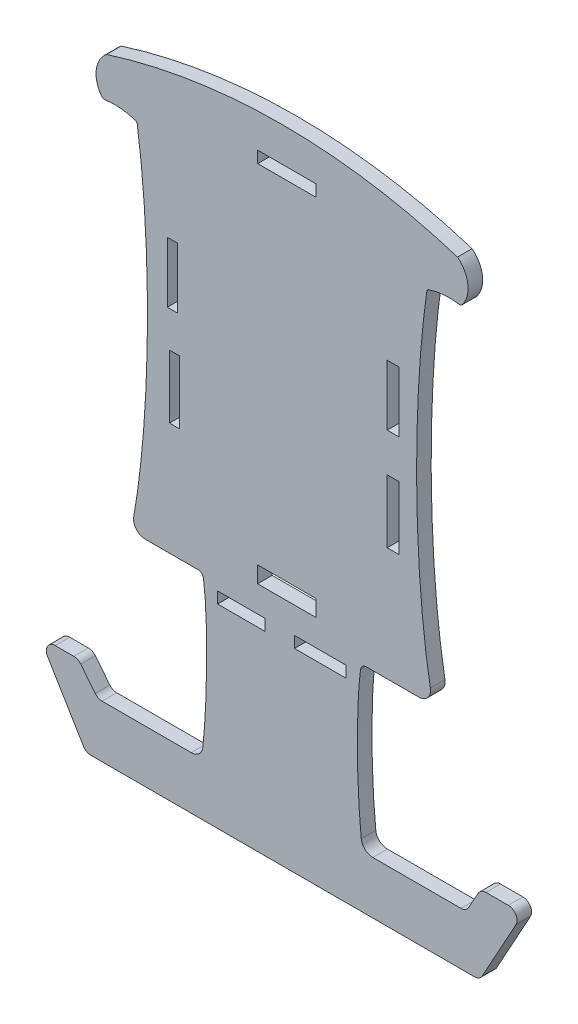
SolidWorks part; units mm, degrees
ref_plane "Front Plane" through (0, 0, 0) normal (0, 0, 1) x (1, 0, 0)
ref_plane "Top Plane" through (0, 0, 0) normal (0, 1, 0) x (1, 0, 0)
ref_plane "Right Plane" through (0, 0, 0) normal (1, 0, 0) x (0, 0, -1)
sketch "Sketch1" plane through (0, 0, 0) normal (0, 0, 1) x (1, 0, 0)
  line L0 (0, -123.7841) -> (0, 123.7841) construction
  line L1 (75.0482, 0) -> (-75.0482, 0) construction
  line L2 (-46.9089, -52.7206) -> (-28.9089, -52.7206)
  line L3 (-48.0489, 48.7999) -> (48.77, 48.7999) construction
  line L4 (-48.0489, 48.7999) -> (-48.0489, -52.7206) construction
  line L5 (-48.0489, -52.7206) -> (46.9089, -52.7206) construction
  line L6 (48.77, 48.7999) -> (48.77, -71.2001) construction
  line L7 (28.9089, -52.7206) -> (46.9089, -52.7206)
  line L8 (27.5, -123.7841) -> (27.5, 123.7841) construction
  line L13 (-27.5, -123.7841) -> (-27.5, 123.7841) construction
  line L14 (-62.2909, -89.7001) -> (10.6178, -89.7001) construction
  line L15 (-61.691, -108.2001) -> (-31.1278, -108.2001)
  line L17 (-65.5309, -126.2001) -> (65.9973, -126.2001)
  line L19 (61.3631, -108.2001) -> (31.1278, -108.2001)
  line L20 (63.9852, -106.6578) -> (67.2823, -100.727)
  line L21 (33.2, -123.7841) -> (33.2, 123.7841) construction
  line L22 (-33.2, -123.7841) -> (-33.2, 123.7841) construction
  line L23 (-68.204, 8.068) -> (119.1983, 8.068) construction
  line L24 (-8.3363, 82.068) -> (11.6637, 82.068)
  line L25 (-8.3363, 82.068) -> (-8.3363, 78.068)
  line L26 (-8.3363, 78.068) -> (11.6637, 78.068)
  line L27 (11.6637, 82.068) -> (11.6637, 78.068)
  line L28 (-8.3363, 8.068) -> (11.6637, 8.068) construction
  line L29 (4.2708, -55.6969) -> (21.9062, -55.6969)
  line L30 (36.0571, 41.9191) -> (40.1596, 41.9191)
  line L31 (36.0571, 41.9191) -> (36.0571, 21.1447)
  line L32 (36.0571, 21.1447) -> (40.1596, 21.1447)
  line L33 (40.1596, 41.9191) -> (40.1596, 21.1447)
  line L34 (36.0571, 7.8806) -> (40.1596, 7.8806)
  line L35 (36.0571, 7.8806) -> (36.0571, -13.7802)
  line L36 (36.0571, -13.7802) -> (40.1596, -13.7802)
  line L37 (40.1596, 7.8806) -> (40.1596, -13.7802)
  line L38 (-35.9066, 40.7148) -> (-39.3248, 40.7148)
  line L39 (-35.9066, 40.7148) -> (-35.9066, 19.9404)
  line L40 (-35.9066, 19.9404) -> (-39.3248, 19.9404)
  line L41 (-39.3248, 40.7148) -> (-39.3248, 19.9404)
  line L42 (-35.1539, 7.5796) -> (-38.5721, 7.5796)
  line L43 (-35.1539, 7.5796) -> (-35.1539, -14.0813)
  line L44 (-35.1539, -14.0813) -> (-38.5721, -14.0813)
  line L45 (-38.5721, 7.5796) -> (-38.5721, -14.0813)
  line L46 (-8.39, -41.0677) -> (11.61, -41.0677)
  line L47 (-8.39, -41.0677) -> (-8.39, -46.6996)
  line L48 (-8.39, -46.6996) -> (11.61, -46.6996)
  line L49 (11.61, -41.0677) -> (11.61, -46.6996)
  line L50 (-22.0905, -55.6841) -> (-5.866, -55.6841)
  line L51 (-22.0905, -55.6841) -> (-22.0905, -59.5639)
  line L52 (-22.0905, -59.5639) -> (-5.866, -59.5639)
  line L53 (-5.866, -55.6841) -> (-5.866, -59.5639)
  line L54 (4.2708, -55.6969) -> (4.2708, -59.5766)
  line L55 (4.2708, -59.5766) -> (21.9062, -59.5766)
  line L56 (21.9062, -55.6969) -> (21.9062, -59.5766)
  line L57 (69.9044, -99.1846) -> (77.5706, -99.1846)
  line L58 (80.1985, -103.6318) -> (68.6251, -124.6473)
  line L59 (-64.0284, -107.0807) -> (-69.0317, -100.8622)
  line L60 (-71.3691, -99.7428) -> (-77.798, -99.7428)
  line L61 (-80.3709, -104.2856) -> (-68.1038, -124.7429)
  arc A2 (-50.8462, -48.0152) -> (-46.9089, -52.7206) centre (-46.9089, -48.7206) ccw
  arc A4 (50.8462, -48.0152) -> (46.9089, -52.7206) centre (46.9089, -48.7206) cw
  arc A10 (-26.9152, -54.4593) -> (-28.9089, -52.7206) centre (-28.9089, -54.733) ccw
  arc A11 (-27.1502, -104.6229) -> (-31.1278, -108.2001) centre (-31.1278, -104.2001) cw
  arc A12 (26.9152, -54.4593) -> (28.9089, -52.7206) centre (28.9089, -54.733) cw
  arc A13 (27.1502, -104.6229) -> (31.1278, -108.2001) centre (31.1278, -104.2001) ccw
  arc A15 (50.3061, 69.9637) -> (60.8253, 70.8473) centre (57.3842, 48.7567) cw
  arc A16 (49.6329, 69.1576) -> (50.3061, 69.9637) centre (50.6227, 69.0151) cw
  arc A23 (-49.6329, 69.1576) -> (-50.3061, 69.9637) centre (-50.6227, 69.0151) ccw
  arc A24 (61.7703, 71.2237) -> (60.1651, 84.5824) centre (54.1859, 77.0882) ccw
  arc A25 (61.7703, 71.2237) -> (60.8253, 70.8473) centre (60.9792, 71.8354) cw
  arc A26 (-61.7703, 71.2237) -> (-60.1651, 84.5824) centre (-54.1859, 77.0882) cw
  arc A27 (-61.7703, 71.2237) -> (-60.8253, 70.8473) centre (-60.9792, 71.8354) ccw
  arc A28 (-50.3061, 69.9637) -> (-60.8253, 70.8473) centre (-57.3842, 48.7567) ccw
  arc A29 (-60.1651, 84.5824) -> (60.1651, 84.5824) centre (0, -105.4386) cw
  arc A30 (68.6251, -124.6473) -> (65.9973, -126.2001) centre (65.9973, -123.2001) cw
  arc A31 (63.9852, -106.6578) -> (61.3631, -108.2001) centre (61.3631, -105.2001) cw
  arc A32 (69.9044, -99.1846) -> (67.2823, -100.727) centre (69.9044, -102.1846) ccw
  arc A33 (77.5706, -99.1846) -> (80.1985, -103.6318) centre (77.5706, -102.1846) cw
  arc A34 (-64.0284, -107.0807) -> (-61.691, -108.2001) centre (-61.691, -105.2001) ccw
  arc A35 (-71.3691, -99.7428) -> (-69.0317, -100.8622) centre (-71.3691, -102.7428) cw
  arc A36 (-80.3709, -104.2856) -> (-77.798, -99.7428) centre (-77.798, -102.7428) cw
  arc A37 (-65.5309, -126.2001) -> (-68.1038, -124.7429) centre (-65.5309, -123.2001) cw
  ellipse E1 centre (-63.6662, 14.31) end of major axis (-63.6573, 105.682) minor radius 17.5396 (-50.8462, -48.0152) -> (-49.6329, 69.1576) ccw
  ellipse E2 centre (63.6662, 14.31) end of major axis (63.6573, 105.682) minor radius 17.5396 (50.8462, -48.0152) -> (49.6329, 69.1576) cw
  ellipse E3 centre (-29.5196, -82.9971) end of major axis (-28.803, -48.6669) minor radius 3.6249 (-27.1502, -104.6229) -> (-26.9152, -54.4593) ccw
  ellipse E4 centre (29.5196, -82.9971) end of major axis (28.803, -48.6669) minor radius 3.6249 (27.1502, -104.6229) -> (26.9152, -54.4593) cw
  point P4 (0, 0)
  point P8 (0, 0)
  point P41 (67.77, -126.2001)
  point P42 (0.2332, -126.2001)
  point P49 (63.1278, -108.2001)
  point P135 (-63.1278, -108.2001)
  point P142 (-67.23, -126.2001)
  dimension "D3" = 3
  dimension "D4" = 1
  dimension "D9" = 32
  dimension "D10" = 2.0124
  dimension "D11" = 4
  dimension "D12" = 4
  dimension "D13" = 18
  dimension "D19" = 1
  dimension "D21" = 3
  dimension "D22" = 3
  dimension "D23" = 3
  dimension "D28" = 3
  dimension "D29" = 3
  dimension "D30" = 3
  dimension "D31" = 3
  dimension "D2" = 120
  dimension "D7" = 18.5
  dimension "D8" = 175
  dimension "D16" = 20
  dimension "D17" = 4
  dimension "D20" = 135
  dimension "D24" = 67.23
  dimension "D25" = 23.9915
  dimension "D26" = 6.7857
  dimension "D27" = 7.6663
  dimension "D5" = 27.5
  dimension "D6" = 27.5
  dimension "D14" = 33.2
  dimension "D15" = 33.2
  dimension "D18" = 70
extrude "Boss-Extrude3" add sketch "Sketch1" along normal blind 5
